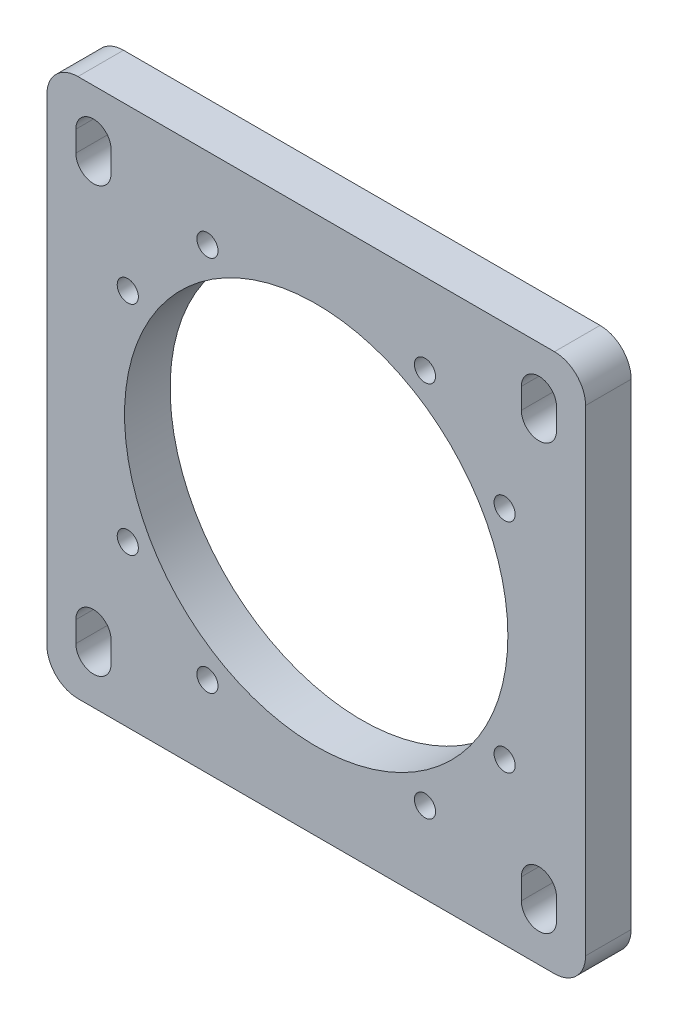
SolidWorks part; units mm, degrees
ref_plane "正面" through (0, 0, 0) normal (0, 0, 1) x (1, 0, 0)
ref_plane "平面" through (0, 0, 0) normal (0, 1, 0) x (1, 0, 0)
ref_plane "右側面" through (0, 0, 0) normal (1, 0, 0) x (0, 0, -1)
sketch "ｽｹｯﾁ1" plane through (0, 0, 0) normal (0, 0, 1) x (1, 0, 0)
  line L1 (-130, -130) -> (130, -130)
  line L2 (-130, -130) -> (-130, 130)
  line L3 (-130, 130) -> (130, 130)
  line L4 (130, -130) -> (130, 130)
extrude "ﾎﾞｽ - 押し出し1" add sketch "ｽｹｯﾁ1" along normal blind 22
fillet "ﾌｨﾚｯﾄ1" radius 15 4 edges at (-130, 130, 11) (130, 130, 11) (130, -130, 11) (-130, -130, 11)
sketch "ｽｹｯﾁ2" plane through (0, 0, 0) normal (0, 0, 1) x (1, 0, 0)
  circle A0 centre (0, 0) radius 92.5
  circle A1 centre (90.9327, 52.5) radius 5.1
  circle A2 centre (52.5, 90.9327) radius 5.1
  circle A3 centre (-52.5, 90.9327) radius 5.1
  circle A4 centre (-90.9327, 52.5) radius 5.1
  circle A5 centre (-90.9327, -52.5) radius 5.1
  circle A6 centre (-52.5, -90.9327) radius 5.1
  circle A7 centre (52.5, -90.9327) radius 5.1
  circle A8 centre (90.9327, -52.5) radius 5.1
extrude "ｶｯﾄ - 押し出し1" cut sketch "ｽｹｯﾁ2" against normal through all and the other way through all
sketch "ｽｹｯﾁ3" plane through (0, 0, 0) normal (0, 0, 1) x (1, 0, 0)
  line L0 (-107.5, -107.5) -> (-107.5, -97.5) construction
  line L1 (-116, -107.5) -> (-116, -97.5)
  line L2 (-99, -107.5) -> (-99, -97.5)
  line L3 (-107.5, 97.5) -> (-107.5, 107.5) construction
  line L4 (-116, 97.5) -> (-116, 107.5)
  line L5 (-99, 97.5) -> (-99, 107.5)
  line L6 (107.5, -107.5) -> (107.5, -97.5) construction
  line L7 (99, -107.5) -> (99, -97.5)
  line L8 (116, -107.5) -> (116, -97.5)
  line L9 (107.5, 97.5) -> (107.5, 107.5) construction
  line L10 (99, 97.5) -> (99, 107.5)
  line L11 (116, 97.5) -> (116, 107.5)
  arc A0 (-116, -107.5) -> (-99, -107.5) centre (-107.5, -107.5) ccw
  arc A1 (-99, -97.5) -> (-116, -97.5) centre (-107.5, -97.5) ccw
  arc A2 (-116, 97.5) -> (-99, 97.5) centre (-107.5, 97.5) ccw
  arc A3 (-99, 107.5) -> (-116, 107.5) centre (-107.5, 107.5) ccw
  arc A4 (99, -107.5) -> (116, -107.5) centre (107.5, -107.5) ccw
  arc A5 (116, -97.5) -> (99, -97.5) centre (107.5, -97.5) ccw
  arc A6 (99, 97.5) -> (116, 97.5) centre (107.5, 97.5) ccw
  arc A7 (116, 107.5) -> (99, 107.5) centre (107.5, 107.5) ccw
  point P2 (-107.5, -102.5)
  point P7 (-107.5, 102.5)
  point P14 (107.5, -102.5)
  point P21 (107.5, 102.5)
  point P28 (0, 0)
extrude "ｶｯﾄ - 押し出し2" cut sketch "ｽｹｯﾁ3" against normal through all and the other way through all
